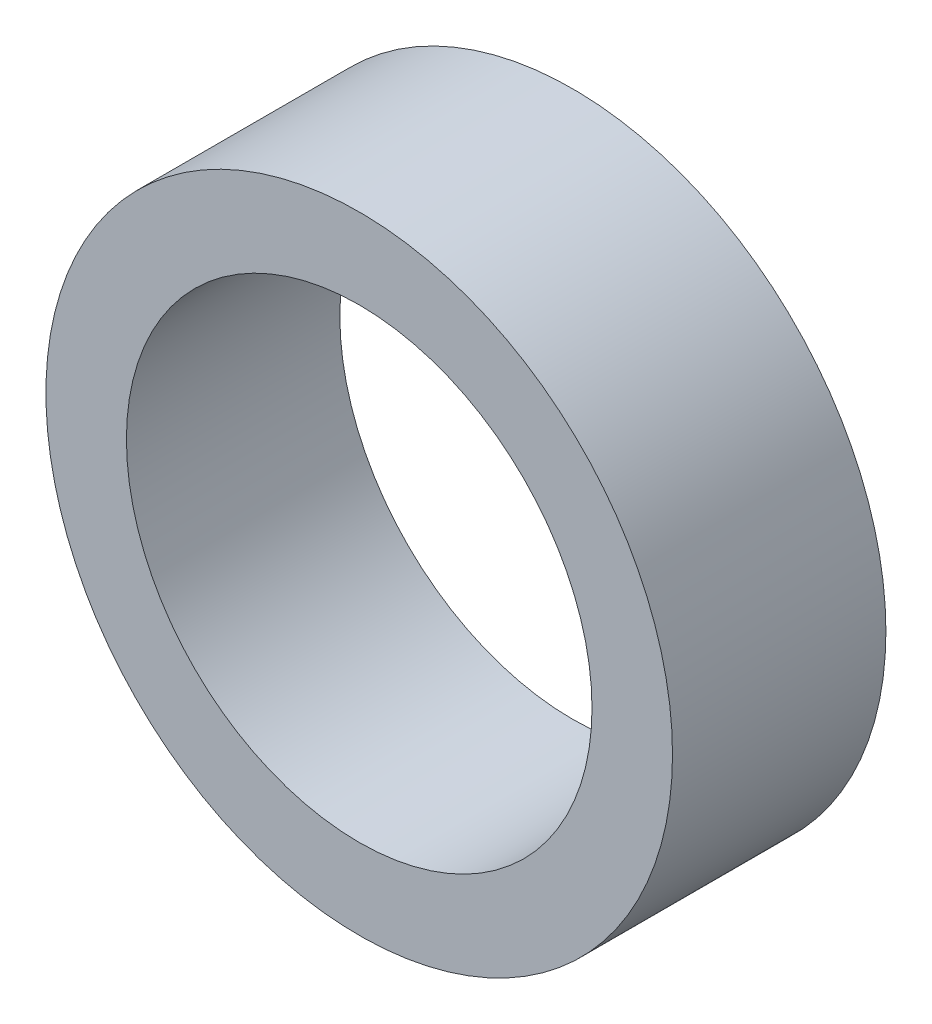
SolidWorks part; units mm, degrees
ref_plane "Plano frontal" through (0, 0, 0) normal (0, 0, 1) x (1, 0, 0)
ref_plane "Plano superior" through (0, 0, 0) normal (0, 1, 0) x (1, 0, 0)
ref_plane "Plano direito" through (0, 0, 0) normal (1, 0, 0) x (0, 0, -1)
sketch "Sketch1" plane through (0, 0, 0) normal (0, 0, 1) x (1, 0, 0)
  circle A0 centre (0, 0) radius 6
  circle A1 centre (0, 0) radius 8.075
  dimension "D1" = 12
  dimension "D2" = 16.15
extrude "Boss-Extrude1" add sketch "Sketch1" along normal blind 5.5
